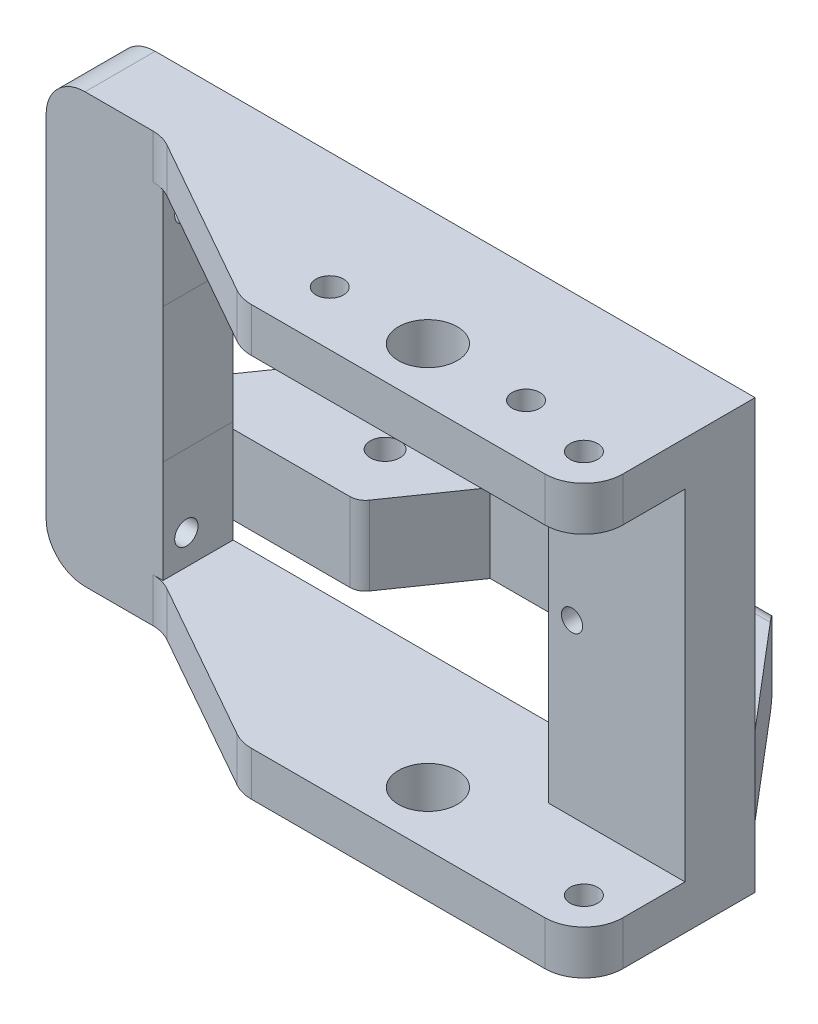
SolidWorks part; units mm, degrees
ref_plane "Front Plane" through (0, 0, 0) normal (0, 0, 1) x (1, 0, 0)
ref_plane "Top Plane" through (0, 0, 0) normal (0, 1, 0) x (1, 0, 0)
ref_plane "Right Plane" through (0, 0, 0) normal (1, 0, 0) x (0, 0, -1)
sketch "Sketch1" plane through (0, 0, 0) normal (0, 0, 1) x (1, 0, 0)
  line L1 (57.15, -34.925) -> (-57.15, -34.925)
  line L2 (57.15, -34.925) -> (57.15, 34.925)
  line L3 (57.15, 34.925) -> (-57.15, 34.925)
  line L4 (-57.15, -34.925) -> (-57.15, 34.925)
  line L5 (57.15, -34.925) -> (-57.15, 34.925) construction
  line L6 (57.15, 34.925) -> (-57.15, -34.925) construction
  point P0 (0, 0)
  dimension "D1" = 69.85
  dimension "D2" = 114.3
extrude "Boss-Extrude1" add sketch "Sketch1" along normal blind 57.15
sketch "Sketch2" plane through (0, 0, 57.15) normal (0, 0, 1) x (1, 0, 0)
  line L0 (-57.15, 34.925) -> (-57.15, -34.925) construction
  line L1 (57.15, -27.725) -> (-57.15, -27.725)
  line L2 (57.15, -27.725) -> (57.15, 27.725)
  line L3 (57.15, 27.725) -> (-57.15, 27.725)
  line L4 (-57.15, -27.725) -> (-57.15, 27.725)
  line L5 (57.15, -27.725) -> (-57.15, 27.725) construction
  line L6 (57.15, 27.725) -> (-57.15, -27.725) construction
  line L7 (57.15, 34.925) -> (-57.15, 34.925) construction
  point P0 (0, 0)
  dimension "D1" = 7.2
extrude "Cut-Extrude2" cut sketch "Sketch2" against normal blind 25.4
sketch "Sketch3" plane through (0, 0, 0) normal (0, 0, -1) x (-1, 0, 0)
  line L0 (-57.15, -34.925) -> (-57.15, 34.925) construction
  line L1 (57.15, 34.925) -> (-57.15, 34.925)
  line L2 (57.15, 34.925) -> (57.15, -12.065)
  line L3 (57.15, -12.065) -> (-57.15, -12.065)
  line L4 (-57.15, 34.925) -> (-57.15, -12.065)
  dimension "D1" = 46.99
extrude "Cut-Extrude3" cut sketch "Sketch3" against normal blind 20.32
sketch "Sketch5" plane through (0, -34.925, 0) normal (0, -1, 0) x (1, 0, 0)
  line L0 (-3.81, 10.79) -> (46.99, 10.79) construction
  line L1 (57.15, 20.32) -> (-57.15, 20.32) construction
  line L2 (57.15, 57.15) -> (57.15, 0) construction
  circle A0 centre (-3.81, 10.79) radius 2.415
  circle A1 centre (46.99, 10.79) radius 2.415
  dimension "D3" = 4.83
  dimension "D4" = 10.16
  dimension "D1" = 9.53
  dimension "D2" = 50.8
sketch "Sketch7" plane through (0, -34.925, 0) normal (0, -1, 0) x (1, 0, 0)
  line L0 (57.15, 57.15) -> (57.15, 0) construction
  line L2 (-57.15, 31.75) -> (57.15, 31.75) construction
  circle A0 centre (31.75, 39.37) radius 4.8
  dimension "D1" = 9.6
  dimension "D2" = 25.4
  dimension "D3" = 7.62
extrude "Cut-Extrude6" cut sketch "Sketch7" against normal up to surface (69.85 mm away) up to face at (0, 34.925, 38.735)
sketch "Sketch8" plane through (0, 34.925, 0) normal (0, 1, 0) x (1, 0, 0)
  line L0 (15.75, -39.37) -> (47.75, -39.37) construction
  line L1 (57.15, -31.75) -> (-57.15, -31.75) construction
  circle A0 centre (31.75, -39.37) radius 16 construction
  circle A1 centre (15.75, -39.37) radius 2.25
  circle A2 centre (47.75, -39.37) radius 2.25
  dimension "D1" = 32
  dimension "D2" = 4.5
  dimension "D3" = 0
sketch "Sketch9" plane through (0, 0, 31.75) normal (0, 0, 1) x (1, 0, 0)
  line L0 (57.15, 34.925) -> (-57.15, 34.925) construction
  line L5 (57.15, 27.725) -> (-57.15, 27.725) construction
  line L6 (-19.05, 27.725) -> (43.815, 27.725)
  line L7 (-19.05, 27.725) -> (-19.05, -27.725)
  line L8 (-19.05, -27.725) -> (43.815, -27.725)
  line L9 (43.815, 27.725) -> (43.815, -27.725)
  line L10 (-57.15, -27.725) -> (57.15, -27.725) construction
  line L11 (-57.15, 27.725) -> (-57.15, -27.725) construction
  line L12 (57.15, -27.725) -> (57.15, 27.725) construction
  line L13 (-57.15, -34.925) -> (-38.1, -34.925)
  line L14 (-57.15, -34.925) -> (-57.15, 34.925)
  line L15 (-57.15, 34.925) -> (-38.1, 34.925)
  line L16 (-38.1, -34.925) -> (-38.1, 34.925)
  line L17 (-57.15, -34.925) -> (-38.1, 34.925) construction
  line L18 (-57.15, 34.925) -> (-38.1, -34.925) construction
  line L19 (-57.15, -34.925) -> (57.15, -34.925) construction
  point P5 (-47.625, 0)
  dimension "D1" = 13.335
  dimension "25in" = 38.1
  dimension "D2" = 19.05
extrude "Cut-Extrude7" cut sketch "Sketch9" against normal through all both and the other way through all
extrude "Cut-Extrude8" cut sketch "Sketch8" against normal up to next
sketch "Sketch12" plane through (-19.05, 0, 0) normal (1, 0, 0) x (0, 0, -1)
  line L0 (-31.75, -27.725) -> (-31.75, 27.725) construction
  line L1 (-27.94, -22.86) -> (-27.94, 22.86) construction
  line L2 (-20.32, 27.725) -> (-20.32, -12.065) construction
  circle A0 centre (-27.94, -22.86) radius 1.905
  circle A1 centre (-27.94, 22.86) radius 1.905
  point P0 (-31.75, 0)
  point P8 (-27.94, 0)
  dimension "D1" = 3.81
  dimension "D2" = 7.62
  dimension "D3" = 45.72
extrude "Cut-Extrude10" cut sketch "Sketch12" against normal up to surface (19.05 mm away) up to face at (-38.1, -2.413, 33.274)
sketch "Sketch13" plane through (0, 34.925, 0) normal (0, 1, 0) x (1, 0, 0)
  line L0 (-38.1, -48.2242) -> (57.15, -48.2242)
  line L2 (57.15, -57.15) -> (-38.1, -57.15) construction
  line L3 (47.75, -39.37) -> (15.75, -39.37) construction
  line L4 (-38.1, -48.2242) -> (-38.1, -57.15)
  line L5 (-38.1, -57.15) -> (57.15, -57.15)
  line L6 (-38.1, -20.32) -> (-38.1, -57.15) construction
  line L7 (57.15, -57.15) -> (57.15, -20.32) construction
  line L8 (57.15, -48.2242) -> (57.15, -57.15)
extrude "Cut-Extrude12" cut sketch "Sketch13" against normal through all
sketch "Sketch14" plane through (43.815, 0, 0) normal (-1, 0, 0) x (0, 0, 1)
  line L0 (0, -27.725) -> (31.75, -27.725) construction
  line L1 (20.32, -12.065) -> (0, -12.065)
  line L2 (20.32, -12.065) -> (20.32, -27.725)
  line L3 (20.32, -27.725) -> (0, -27.725)
  line L4 (0, -12.065) -> (0, -27.725)
extrude "Boss-Extrude2" add sketch "Sketch14" along normal up to next
sketch "Sketch18" plane through (-38.1, 0, 0) normal (-1, 0, 0) x (0, 0, 1)
  line L0 (0, -34.925) -> (48.2242, -34.925) construction
  line L1 (20.32, -35.0627) -> (20.32, -24.9001)
  line L2 (20.32, -24.9001) -> (0, -24.9001)
  line L3 (0, -34.925) -> (0, -12.065) construction
  line L4 (0, -24.9001) -> (0, -34.925)
  line L5 (20.32, -34.925) -> (0, -34.925)
  point P0 (20.32, -34.925)
  point P1 (7.9478, 3.6724)
  line M3 (0, -34.925) -> (48.2242, -34.925)
  line M12 (0, -12.065) -> (0, -34.925)
extrude "Cut-Extrude20" cut sketch "Sketch5" against normal through all contours A0 | A1
extrude "Cut-Extrude21" cut sketch "Sketch18" against normal through all contours L1 L2 M12 M3
sketch "Sketch26" plane through (57.15, 0, 0) normal (1, 0, 0) x (0, 0, -1)
  line L28 (-48.2242, -34.925) -> (-20.32, -34.925)
  line L29 (-20.32, -34.925) -> (-20.32, -24.9001)
  line L30 (-20.32, -24.9001) -> (0, -24.9001)
  line L31 (0, -24.9001) -> (0, -12.065)
  line L32 (0, -12.065) -> (-20.32, -12.065)
  line L33 (-20.32, -12.065) -> (-20.32, 34.925)
  line L34 (-20.32, 34.925) -> (-48.2242, 34.925)
  line L35 (-48.2242, 34.925) -> (-48.2242, 27.725)
  line L36 (-48.2242, 27.725) -> (-31.75, 27.725)
  line L37 (-31.75, 27.725) -> (-31.75, -27.725)
  line L40 (-31.75, -27.725) -> (-48.2242, -27.725)
  line L41 (-48.2242, -27.725) -> (-48.2242, -34.925)
  line L42 (-48.2242, -34.925) -> (-20.32, -34.925)
  line L43 (-20.32, -34.925) -> (-20.32, -24.9001)
  line L44 (-20.32, -24.9001) -> (0, -24.9001)
  line L45 (0, -24.9001) -> (0, -12.065)
  line L46 (0, -12.065) -> (-20.32, -12.065)
  line L47 (-20.32, -12.065) -> (-20.32, 34.925)
  line L48 (-20.32, 34.925) -> (-48.2242, 34.925)
  line L49 (-48.2242, 34.925) -> (-48.2242, 27.725)
  line L50 (-48.2242, 27.725) -> (-31.75, 27.725)
  line L51 (-31.75, 27.725) -> (-31.75, -27.725)
  line L54 (-31.75, -27.725) -> (-48.2242, -27.725)
  line L55 (-48.2242, -27.725) -> (-48.2242, -34.925)
  dimension "D1" = 0
extrude "Boss-Extrude4" add sketch "Sketch26" along normal blind 8.89
sketch "Sketch31" plane through (0, 34.925, 0) normal (0, 1, 0) x (1, 0, 0)
  line L0 (66.04, -48.2242) -> (-38.1, -48.2242) construction
  line L1 (66.04, -20.32) -> (66.04, -48.2242) construction
  point P0 (59.69, -41.8742)
  dimension "D1" = 6.35
  dimension "D2" = 6.35
hole_wizard "#8 Clearance Hole1" positions "Sketch31" profile "Sketch30" hole size "#8" standard "ANSI Inch" end condition through all
sketch "Sketch30" plane through (59.69, 34.925, 41.8742) normal (1, 0, 0) x (0, 0, 1)
  line L0 (0, 0) -> (0, 69.85)
  line L1 (0, 69.85) -> (2.2479, 69.85)
  line L2 (2.2479, 69.85) -> (2.2479, 0)
  line L5 (2.2479, 0) -> (0, 0)
  line L11 (0, -6.35) -> (0, 107.95) construction
  dimension "Thru Hole Dia." = 4.4958
  dimension "Thru Hole Depth" = 69.85
sketch "Sketch38" plane through (0, 0, 31.75) normal (0, 0, 1) x (1, 0, 0)
  line L0 (43.815, -27.725) -> (43.815, 27.725) construction
  line L2 (47.625, 0) -> (43.815, 0) construction
  point P0 (47.625, 0)
  dimension "D1" = 3.81
hole_wizard "#8-32 Tapped Hole1" positions "Sketch38" profile "Sketch37" tap size "#8-32" standard "ANSI Inch" end condition through all
sketch "Sketch37" plane through (47.625, 0, 31.75) normal (1, 0, 0) x (0, -1, 0)
  line L0 (0, 0) -> (0, 31.75)
  line L1 (0, 31.75) -> (1.7272, 31.75)
  line L2 (1.7272, 31.75) -> (1.7272, 0)
  line L5 (1.7272, 0) -> (0, 0)
  line L11 (0, -6.35) -> (0, 107.95) construction
  dimension "Thru Tap Drill Dia." = 3.4544
  dimension "Thru Tap Drill Depth" = 31.75
cosmetic thread "Hole Thread1" parameters "D2"=4.1656
sketch "Sketch40" plane through (0, 0, 0) normal (0, 0, -1) x (-1, 0, 0)
  line L1 (-66.04, -12.065) -> (38.1, -12.065)
  line L2 (-66.04, -12.065) -> (-66.04, -24.9001)
  line L3 (-66.04, -24.9001) -> (38.1, -24.9001)
  line L4 (38.1, -12.065) -> (38.1, -24.9001)
extrude "Cut-Extrude22" cut sketch "Sketch40" against normal blind 1.27
sketch "Sketch42" plane through (0, 0, 20.32) normal (0, 0, -1) x (-1, 0, 0)
  line L0 (38.1, -12.065) -> (38.1, 34.925) construction
  line L1 (-66.04, -12.065) -> (38.1, -12.065)
  line L2 (-66.04, -12.065) -> (-66.04, 9.7254)
  line L3 (-66.04, 9.7254) -> (38.1, 9.7254)
  line L4 (38.1, -12.065) -> (38.1, 9.7254)
split line "Split Line1" [suppressed]
sketch "Sketch43" plane through (-19.05, 0, 0) normal (1, 0, 0) x (0, 0, -1)
  line L0 (-31.75, 27.725) -> (-31.75, -27.725) construction
  line L1 (-20.32, -10.9992) -> (-31.75, -10.9992)
  line L2 (-20.32, -10.9992) -> (-20.32, 10.945)
  line L3 (-20.32, 10.945) -> (-31.75, 10.945)
  line L4 (-31.75, -10.9992) -> (-31.75, 10.945)
  line L5 (-20.32, -10.9992) -> (-31.75, 10.945) construction
  line L6 (-20.32, 10.945) -> (-31.75, -10.9992) construction
  line L7 (-31.75, 0) -> (-20.32, 0) construction
  line L8 (-20.32, 27.725) -> (-20.32, -12.065) construction
  point P0 (-26.035, -0.0271)
split line "Split Line2"
sketch "Sketch44" plane through (43.815, 0, 0) normal (-1, 0, 0) x (0, 0, 1)
  line L0 (31.75, -27.725) -> (31.75, 27.725) construction
  line L1 (31.75, 6.35) -> (20.32, 6.35)
  line L2 (31.75, 6.35) -> (31.75, -6.35)
  line L3 (31.75, -6.35) -> (20.32, -6.35)
  line L4 (20.32, 6.35) -> (20.32, -6.35)
  line L5 (20.32, -12.065) -> (20.32, 27.725) construction
  point P8 (31.75, 0)
  point P9 (31.75, 0)
  dimension "D1" = 12.7
  dimension "D2" = 0
split line "Split Line3"
sketch "Sketch45" plane through (0, 0, 20.32) normal (0, 0, -1) x (-1, 0, 0)
  line L0 (38.1, -12.065) -> (38.1, 34.925) construction
  line L1 (-66.04, -12.065) -> (38.1, -12.065)
  line L2 (-66.04, -12.065) -> (-66.04, 4.495)
  line L3 (-66.04, 4.495) -> (38.1, 4.495)
  line L4 (38.1, -12.065) -> (38.1, 4.495)
  dimension "D1" = 16.56
split line "Split Line4"
sketch "Sketch47" plane through (0, 34.925, 0) normal (0, 1, 0) x (1, 0, 0)
  line L0 (-38.1, -31.75) -> (-19.05, -31.75)
  line L1 (-19.05, -31.75) -> (10.16, -48.2242)
  line L3 (-38.1, -31.75) -> (-38.1, -48.2242)
  line L4 (-38.1, -48.2242) -> (10.16, -48.2242)
  dimension "D1" = 48.26
extrude "Cut-Extrude24" cut sketch "Sketch47" against normal through all
fillet "Fillet3" radius 6.35 8 edges at (-38.1, 34.925, 26.035) (-38.1, -34.925, 26.035) (-19.05, -31.325, 31.75) (10.16, -31.325, 48.2242) (66.04, -31.325, 48.2242) (66.04, 31.325, 48.2242) (-19.05, 31.325, 31.75) (10.16, 31.325, 48.2242)
sketch "Sketch49" plane through (0, -24.9001, 0) normal (0, -1, 0) x (1, 0, 0)
  line L0 (-38.1, 20.32) -> (-32.3028, 20.32)
  line L1 (66.04, 20.32) -> (-31.75, 20.32) construction
  line L2 (-32.3028, 20.32) -> (-19.0502, 1.27)
  line L3 (66.04, 1.27) -> (-38.1, 1.27) construction
  line L4 (-19.0502, 1.27) -> (-38.1, 1.27)
  line L5 (-38.1, 1.27) -> (-38.1, 20.32)
  line L6 (1.325, 20.32) -> (10.16, 7.62)
  line L7 (10.16, 7.62) -> (33.02, 7.62)
  line L8 (33.02, 7.62) -> (43.815, 20.32)
  line L9 (43.815, 20.32) -> (1.325, 20.32)
  line L10 (66.04, 20.32) -> (49.8475, 1.27)
  line L11 (49.8475, 1.27) -> (66.04, 1.27)
  line L12 (66.04, 1.27) -> (66.04, 20.32)
  line L13 (-3.81, 10.79) -> (46.99, 10.79) construction
  line L14 (43.815, 20.32) -> (-19.05, 20.32) construction
  point P16 (21.59, 10.79)
  point P23 (21.59, 7.62)
  dimension "D5" = 6.35
extrude "Cut-Extrude25" cut sketch "Sketch49" against normal through all
fillet "Fillet4" radius 2.54 7 edges at (15.3986, -24.9001, 1.27) (49.8475, -18.4825, 1.27) (15.3986, -12.065, 1.27) (-19.0502, -18.4825, 1.27) (33.02, -18.4825, 7.62) (1.325, -18.4825, 20.32) (-32.3028, -18.4825, 20.32)
